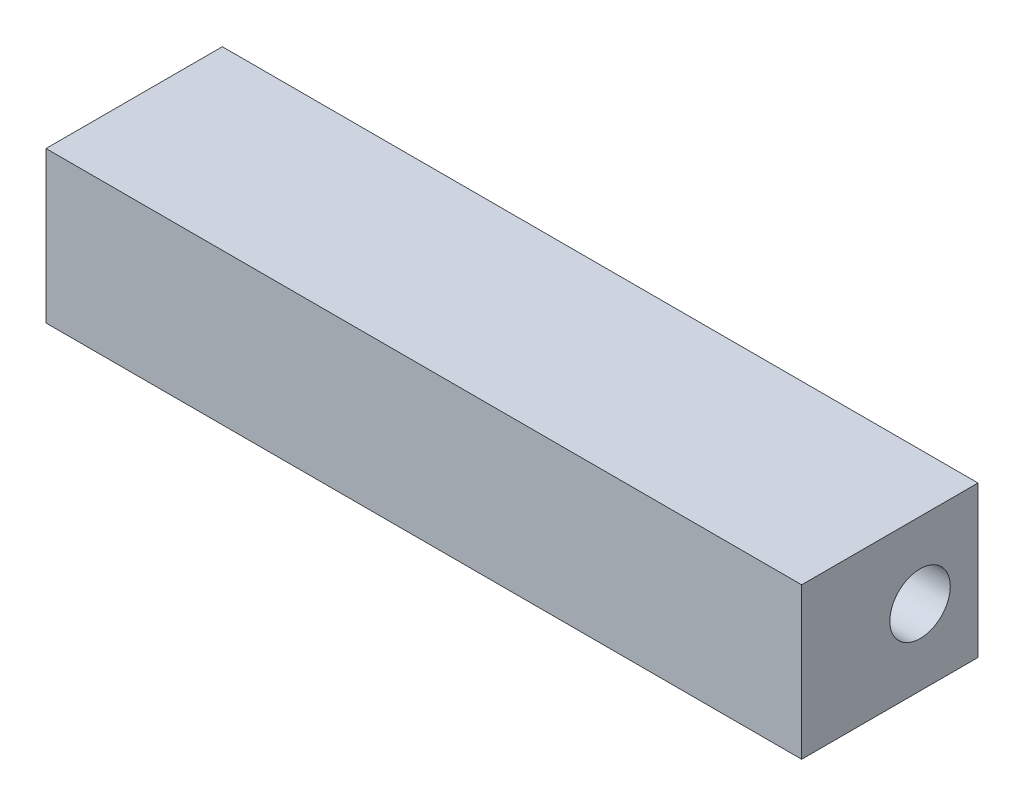
SolidWorks part; units mm, degrees
ref_plane "Спереди" through (0, 0, 0) normal (0, 0, 1) x (1, 0, 0)
ref_plane "Сверху" through (0, 0, 0) normal (0, 1, 0) x (1, 0, 0)
ref_plane "Справа" through (0, 0, 0) normal (1, 0, 0) x (0, 0, -1)
sketch "Эскиз1" plane through (0, 0, 0) normal (0, 1, 0) x (1, 0, 0)
  line L1 (99.6046, 22.8076) -> (-50.3954, 22.8076)
  line L2 (99.6046, 22.8076) -> (99.6046, -12.1924)
  line L3 (99.6046, -12.1924) -> (-50.3954, -12.1924)
  line L4 (-50.3954, 22.8076) -> (-50.3954, -12.1924)
  dimension "D1" = 35
extrude "Бобышка-Вытянуть1" add sketch "Эскиз1" along normal blind 30 contours L1 L4 L3 L2
sketch "Эскиз2" plane through (99.6046, 0, 0) normal (1, 0, 0) x (0, 0, -1)
  line L0 (-12.1924, 30) -> (22.8076, 0) construction
  line L1 (22.8076, 0) -> (-12.1924, 0) construction
  line L2 (11.3076, 30) -> (11.3076, 0) construction
  line L3 (22.8076, 30) -> (-12.1924, 0) construction
  line L4 (22.8076, 30) -> (-12.1924, 30) construction
  circle A0 centre (11.3076, 15) radius 6
  point P8 (5.3076, 15)
  point P19 (11.6365, 25.0879)
  point P20 (15.0831, 25.385)
  point P21 (9.9528, 24.7097)
  point P22 (10.1834, 24.7293)
  dimension "D1" = 6
sketch "Эскиз3" plane through (0, 0, -22.8076) normal (0, 0, -1) x (-1, 0, 0)
  line L0 (-64.6046, 30) -> (-64.6046, 0) construction
  line L1 (-99.6046, 30) -> (50.3954, 30) construction
  line L2 (-99.6046, 0) -> (50.3954, 0) construction
  line L3 (-99.6046, 30) -> (-99.6046, 0) construction
  line L4 (-64.6046, 25) -> (15.3954, 25)
  line L5 (-64.6046, 25) -> (-64.6046, 0)
  line L6 (-64.6046, 0) -> (15.3954, 0)
  line L7 (15.3954, 25) -> (15.3954, 0)
  dimension "D1" = 35
  dimension "D2" = 115
  dimension "D3" = 25
extrude "Вырез-Вытянуть3" cut sketch "Эскиз2" against normal blind 20
extrude "Вырез-Вытянуть2" cut sketch "Эскиз3" against normal blind 15
sketch "Эскиз5" plane through (79.6046, 0, 0) normal (1, 0, 0) x (0, 0, -1)
  circle A0 centre (11.3076, 15) radius 10
extrude "Вырез-Вытянуть6" cut sketch "Эскиз5" against normal blind 95 contours A0
sketch "Эскиз6" plane through (-15.3954, 0, 0) normal (1, 0, 0) x (0, 0, -1)
  circle A0 centre (11.3076, 15) radius 6
extrude "Вырез-Вытянуть7" cut sketch "Эскиз6" against normal blind 25
